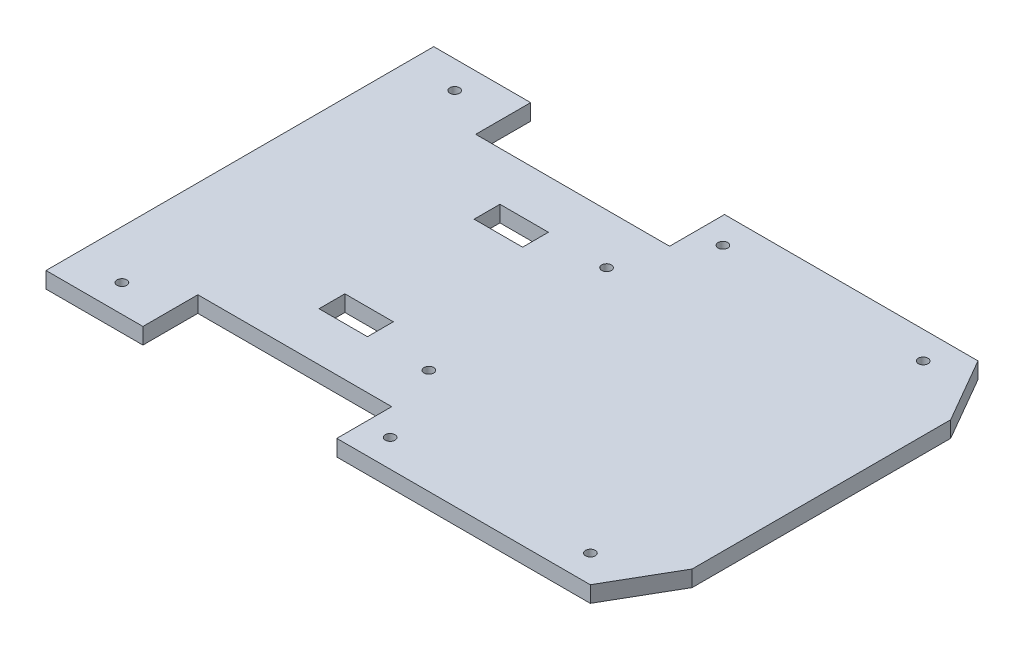
SolidWorks part; units mm, degrees
ref_plane "Plan de face" through (0, 0, 0) normal (0, 0, 1) x (1, 0, 0)
ref_plane "Plan de dessus" through (0, 0, 0) normal (0, 1, 0) x (1, 0, 0)
ref_plane "Plan de droite" through (0, 0, 0) normal (1, 0, 0) x (0, 0, -1)
sketch "Esquisse1" plane through (0, 0, 0) normal (0, 1, 0) x (1, 0, 0)
  line L0 (78.453, 60) -> (90, 40)
  line L1 (-90, 0) -> (90, 0)
  line L2 (-90, 0) -> (-90, 60)
  line L3 (-90, 60) -> (-60, 60)
  line L4 (90, 0) -> (90, 40)
  line L5 (-60, 60) -> (-60, 43)
  line L6 (-60, 43) -> (0, 43)
  line L7 (0, 43) -> (0, 60)
  line L8 (0, 60) -> (78.453, 60)
  line L9 (-60, 51.5) -> (-90, 51.5) construction
  line L10 (-37.5, 28) -> (-22.5, 28)
  line L11 (-37.5, 28) -> (-37.5, 20)
  line L12 (-37.5, 20) -> (-22.5, 20)
  line L13 (-22.5, 28) -> (-22.5, 20)
  circle A0 centre (-75, 51.5) radius 1.5
  circle A1 centre (8, 51.5) radius 1.5
  circle A2 centre (70, 51.5) radius 1.5
  circle A3 centre (-4, 27.5) radius 1.5
  point P8 (-30, 43)
  point P15 (-30, 28)
  point P21 (-75, 60)
  point P26 (0, 51.5)
  dimension "D11" = 3
  dimension "D14" = 15.5
  dimension "D1" = 60
  dimension "D2" = 180
  dimension "D3" = 120
  dimension "D4" = 40
  dimension "D5" = 60
  dimension "D6" = 17
  dimension "D7" = 120
  dimension "D8" = 15
  dimension "D9" = 8
  dimension "D10" = 15
  dimension "D12" = 8
  dimension "D13" = 20
  dimension "D15" = 4
extrude "Boss.-Extru.1" add sketch "Esquisse1" along normal blind 5
mirror "Symétrie1" about plane through (-90, 5, 0) normal (0, 0, -1) of "Boss.-Extru.1"
